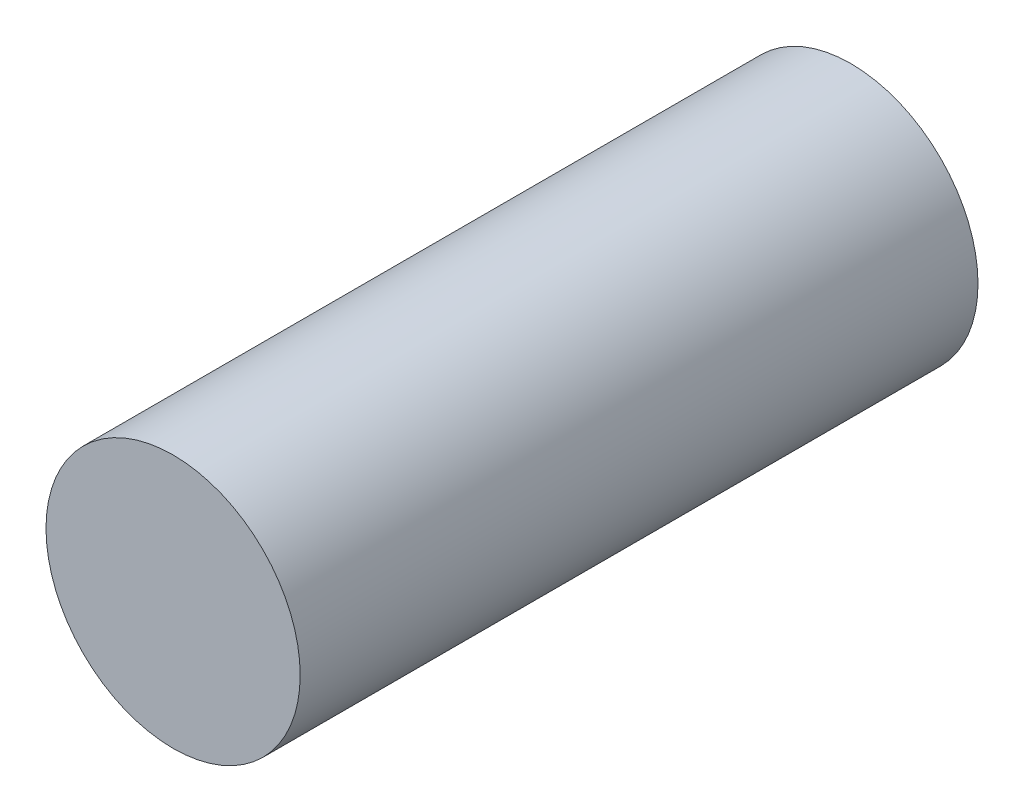
SolidWorks part; units mm, degrees
ref_plane "Front Plane" through (0, 0, 0) normal (0, 0, 1) x (1, 0, 0)
ref_plane "Top Plane" through (0, 0, 0) normal (0, 1, 0) x (1, 0, 0)
ref_plane "Right Plane" through (0, 0, 0) normal (1, 0, 0) x (0, 0, -1)
sketch "Sketch1" plane through (0, 0, 0) normal (0, 0, 1) x (1, 0, 0)
  circle A0 centre (0, 0) radius 3
extrude "Envelope" add sketch "Sketch1" along normal blind 16
